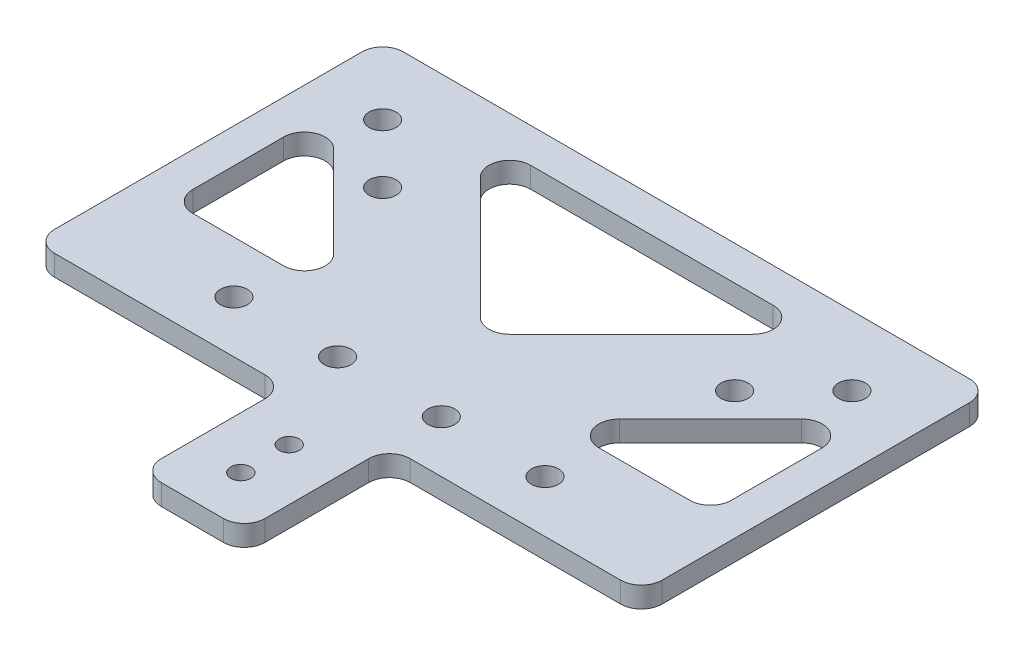
SolidWorks part; units mm, degrees
material "Thornel Mat VMA"
ref_plane "前视基准面" through (0, 0, 0) normal (0, 0, 1) x (1, 0, 0)
ref_plane "上视基准面" through (0, 0, 0) normal (0, 1, 0) x (1, 0, 0)
ref_plane "右视基准面" through (0, 0, 0) normal (1, 0, 0) x (0, 0, -1)
other "Configuration Table"
sketch "草图2" plane through (0, 0, 0) normal (0, 1, 0) x (1, 0, 0)
  line L0 (-96.6798, 0) -> (115.2535, 0) construction
  line L1 (-43.9411, -7.5) -> (43.9411, -7.5) construction
  line L2 (-43.9411, -7.5) -> (-43.9411, 7.5)
  line L3 (-43.9411, 7.5) -> (43.9411, 7.5) construction
  line L4 (43.9411, -7.5) -> (43.9411, 7.5)
  line L5 (-43.9411, -7.5) -> (43.9411, 7.5) construction
  line L6 (-43.9411, 7.5) -> (43.9411, -7.5) construction
  line L7 (0, 90.4424) -> (0, -51.8351) construction
  line L8 (80.1668, 79.1816) -> (0, -0.9853) construction
  line L9 (8.4853, 7.5) -> (0, -0.9853) construction
  line L10 (38.9411, 30.8848) -> (15.5563, 7.5)
  line L11 (-43.9411, 7.5) -> (43.9411, 7.5) construction
  line L12 (-43.9411, 7.5) -> (-43.9411, 42.9558)
  line L13 (-43.9411, 42.9558) -> (43.9411, 42.9558)
  line L14 (43.9411, 7.5) -> (43.9411, 42.9558)
  line L15 (15.5563, 7.5) -> (38.9411, 7.5)
  line L16 (38.9411, 7.5) -> (38.9411, 30.8848)
  line L17 (-15.5563, 7.5) -> (-38.9411, 7.5)
  line L18 (-38.9411, 7.5) -> (-38.9411, 30.8848)
  line L19 (-38.9411, 30.8848) -> (-15.5563, 7.5)
  line L20 (24.799, 37.9558) -> (0, 13.1569)
  line L21 (24.799, 37.9558) -> (-24.799, 37.9558)
  line L22 (-24.799, 37.9558) -> (0, 13.1569)
  line L23 (-43.9411, -7.5) -> (-7.5, -7.5)
  line L24 (-7.5, -7.5) -> (7.5, -7.5) construction
  line L28 (7.5, -7.5) -> (43.9411, -7.5)
  line L29 (-7.5, -7.5) -> (7.5, -7.5) construction
  line L31 (-7.5, -7.5) -> (7.5, -7.5) construction
  line L32 (-7.5, -7.5) -> (-7.5, -28.5)
  line L33 (-7.5, -28.5) -> (7.5, -28.5)
  line L34 (7.5, -7.5) -> (7.5, -28.5)
  circle A0 centre (25.4558, 24.4706) radius 1.95
  circle A1 centre (33.9411, 32.9558) radius 1.95
  circle A2 centre (7.5, 0) radius 1.95
  circle A3 centre (22.5, 0) radius 1.95
  circle A4 centre (-33.9411, 32.9558) radius 1.95
  circle A5 centre (-25.4558, 24.4706) radius 1.95
  circle A6 centre (-22.5, 0) radius 1.95
  circle A7 centre (-7.5, 0) radius 1.95
  circle A8 centre (0, -14.5) radius 1.45
  circle A9 centre (0, -21.5) radius 1.45
  point P0 (0, 0)
  point P41 (0, 37.9558)
  dimension "D3" = 24
  dimension "D4" = 12
  dimension "D5" = 3.9
  dimension "D6" = 7.5
  dimension "D7" = 15
  dimension "D8" = 15
  dimension "D9" = 10
  dimension "D10" = 10
  dimension "D17" = 2.9
  dimension "D18" = 7
  dimension "D19" = 7
  dimension "D1" = 45
  dimension "D2" = 12
  dimension "D11" = 5
  dimension "D12" = 5
  dimension "D13" = 10
  dimension "D14" = 5
  dimension "D15" = 15
  dimension "D16" = 21
extrude "凸台-拉伸3" add sketch "草图2" along normal blind 3
fillet "圆角2" radius 3 17 edges at (-24.799, 1.5, -37.9558) (0, 1.5, -13.1569) (24.799, 1.5, -37.9558) (38.9411, 1.5, -30.8848) (15.5563, 1.5, -7.5) (38.9411, 1.5, -7.5) (-43.9411, 1.5, -42.9558) (-38.9411, 1.5, -30.8848) (-38.9411, 1.5, -7.5) (-15.5563, 1.5, -7.5) (43.9411, 1.5, -42.9558) (43.9411, 1.5, 7.5) (-43.9411, 1.5, 7.5) (-7.5, 1.5, 28.5) (-7.5, 1.5, 7.5) (7.5, 1.5, 28.5) (7.5, 1.5, 7.5)
